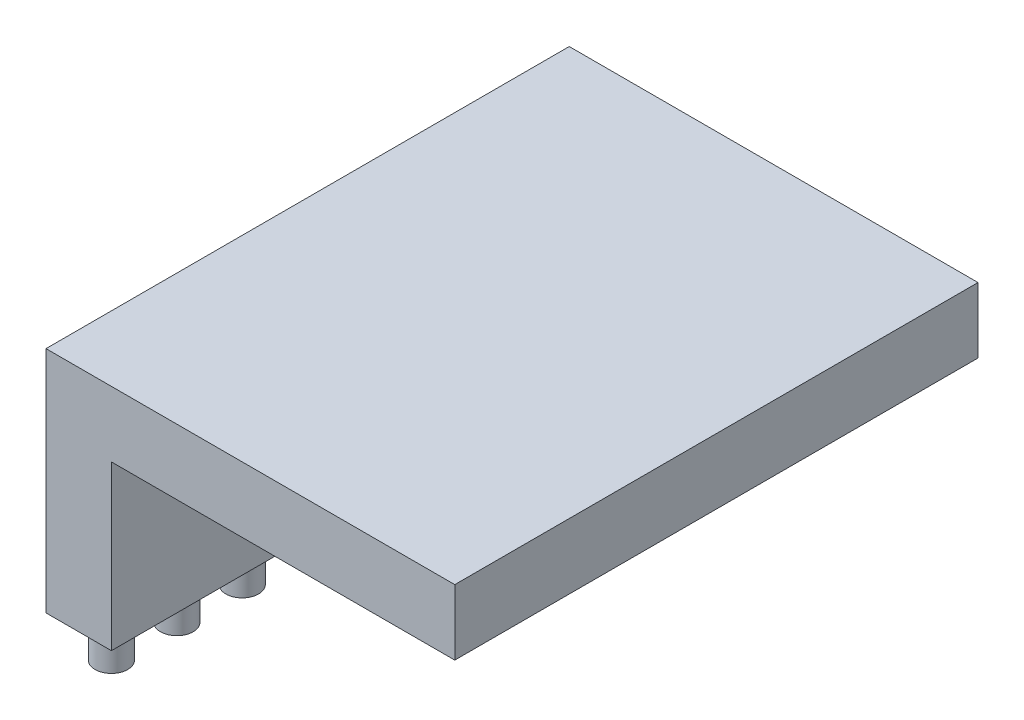
SolidWorks part; units mm, degrees
ref_plane "Front Plane" through (0, 0, 0) normal (0, 0, 1) x (1, 0, 0)
ref_plane "Top Plane" through (0, 0, 0) normal (0, 1, 0) x (1, 0, 0)
ref_plane "Right Plane" through (0, 0, 0) normal (1, 0, 0) x (0, 0, -1)
sketch "Sketch1" plane through (0, 0, 0) normal (0, 1, 0) x (1, 0, 0)
  line L1 (0, 0) -> (-15.875, 0)
  line L2 (0, 0) -> (0, 20.32)
  line L3 (0, 20.32) -> (-15.875, 20.32)
  line L4 (-15.875, 0) -> (-15.875, 20.32)
  dimension "D1" = 20.32
  dimension "D2" = 15.875
extrude "Boss-Extrude1" add sketch "Sketch1" along normal blind 2.54
sketch "Sketch2" plane through (0, 0, 0) normal (0, -1, 0) x (1, 0, 0)
  line L0 (0, -20.32) -> (-15.875, -20.32) construction
  line L1 (-15.875, 0) -> (-13.335, 0)
  line L2 (-15.875, 0) -> (-15.875, -20.32)
  line L3 (-15.875, -20.32) -> (-13.335, -20.32)
  line L4 (-13.335, 0) -> (-13.335, -20.32)
  dimension "D1" = 2.54
extrude "Boss-Extrude2" add sketch "Sketch2" along normal blind 6.35
sketch "Sketch3" plane through (0, -6.35, 0) normal (0, -1, 0) x (1, 0, 0)
  line L0 (-13.335, 0) -> (-15.875, 0) construction
  circle A0 centre (-14.605, -1.27) radius 0.635
  circle A1 centre (-14.605, -3.81) radius 0.635
  circle A2 centre (-14.605, -6.35) radius 0.635
  circle A3 centre (-14.605, -8.89) radius 0.635
  circle A4 centre (-14.605, -11.43) radius 0.635
  circle A5 centre (-14.605, -13.97) radius 0.635
  circle A6 centre (-14.605, -16.51) radius 0.635
  circle A7 centre (-14.605, -19.05) radius 0.635
  point P4 (-14.605, 0)
  dimension "D1" = 1.27
  dimension "D2" = 1.27
  dimension "D3" = 8
extrude "Boss-Extrude3" add sketch "Sketch3" along normal blind 1.5875
